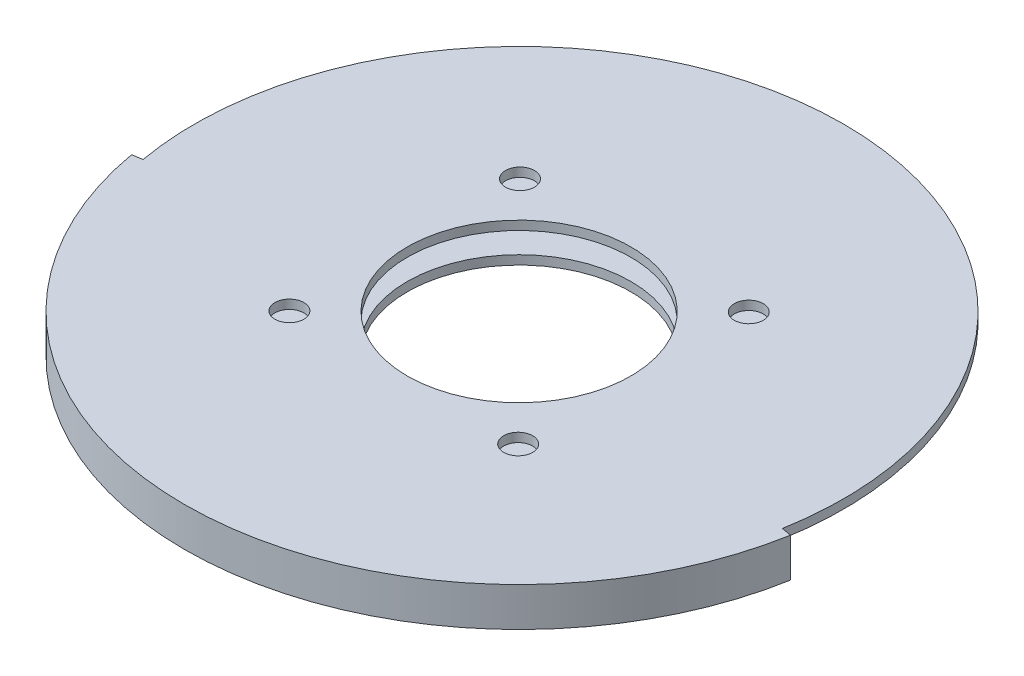
SolidWorks part; units mm, degrees
ref_plane "前视基准面" through (0, 0, 0) normal (0, 0, 1) x (1, 0, 0)
ref_plane "上视基准面" through (0, 0, 0) normal (0, 1, 0) x (1, 0, 0)
ref_plane "右视基准面" through (0, 0, 0) normal (1, 0, 0) x (0, 0, -1)
other "Configuration Table"
sketch "草图1" plane through (0, 477.4044, 0) normal (0, 1, 0) x (1, 0, 0)
  circle A0 centre (0, 0) radius 32.5
extrude "凸台-拉伸1" add sketch "草图1" along normal blind 0.9
sketch "草图2" plane through (0, 478.3044, 0) normal (0, 1, 0) x (1, 0, 0)
  line L0 (0, 0) -> (-32.0063, -5.6436) construction
  line L1 (-32.5, 0) -> (32.5, 0) construction
  line L2 (0, 0) -> (32.0063, -5.6436) construction
  arc A0 (-32.0063, -5.6436) -> (32.0063, -5.6436) centre (0, 0) ccw
  dimension "D1" = 32.5
  dimension "D2" = 10
  dimension "D3" = 10
extrude "拉伸-薄壁1" add sketch "草图2" against normal blind 3.9 thin
sketch "草图3" plane through (0, 474.4044, 0) normal (0, -1, 0) x (1, 0, 0)
  circle A0 centre (0, 0) radius 29
extrude "凸台-拉伸2" add sketch "草图3" against normal blind 0.9
sketch "草图4" plane through (0, 474.4044, 0) normal (0, -1, 0) x (1, 0, 0)
  line L0 (0, 0) -> (-32.0063, 5.6436) construction
  line L1 (-32.5, 0) -> (32.5, 0) construction
  line L2 (0, 0) -> (32.0063, 5.6436) construction
  arc A0 (32.0063, 5.6436) -> (-32.0063, 5.6436) centre (0, 0) ccw
  dimension "D1" = 10
  dimension "D2" = 10
extrude "拉伸-薄壁2" add sketch "草图4" against normal blind 0.9 thin thin type one direction reverse wall 3.5
sketch "草图5" plane through (0, 478.3044, 0) normal (0, 1, 0) x (1, 0, 0)
  circle A0 centre (11.5457, 11.4541) radius 1.45 construction
  circle A1 centre (11.4541, -11.5457) radius 1.45 construction
  circle A2 centre (-11.5457, -11.4541) radius 1.45 construction
  circle A3 centre (-11.4541, 11.5457) radius 1.45 construction
  circle A4 centre (0, 0) radius 11.2 construction
  circle A5 centre (11.5457, 11.4541) radius 1.45
  circle A6 centre (11.4541, -11.5457) radius 1.45
  circle A7 centre (-11.5457, -11.4541) radius 1.45
  circle A8 centre (-11.4541, 11.5457) radius 1.45
  circle A9 centre (0, 0) radius 11.2
extrude "切除-拉伸1" cut sketch "草图5" against normal blind 3.9
